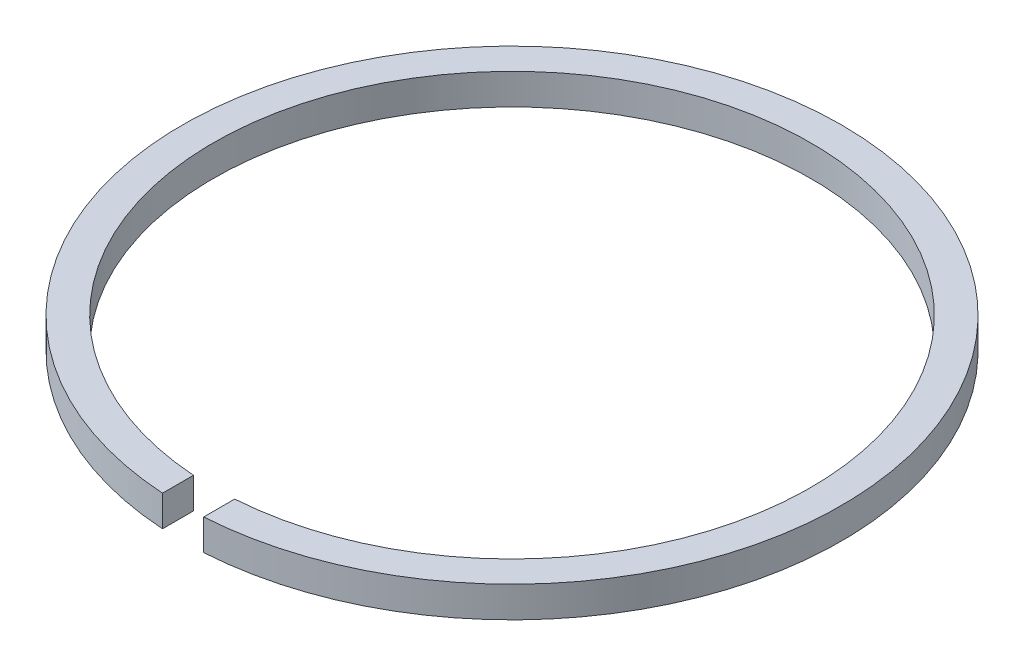
SolidWorks part; units mm, degrees
ref_plane "Front Plane" through (0, 0, 0) normal (0, 0, 1) x (1, 0, 0)
ref_plane "Top Plane" through (0, 0, 0) normal (0, 1, 0) x (1, 0, 0)
ref_plane "Right Plane" through (0, 0, 0) normal (1, 0, 0) x (0, 0, -1)
sketch "Sketch1" plane through (0, 0, 0) normal (0, 1, 0) x (1, 0, 0)
  line L0 (0, 17.4037) -> (0, -20.3096) construction
  line L1 (-1, -14.4655) -> (-1, -15.9687)
  line L2 (1, -14.4655) -> (1, -15.9687)
  arc A0 (1, -15.9687) -> (-1, -15.9687) centre (0, 0) ccw
  arc A1 (1, -14.4655) -> (-1, -14.4655) centre (0, 0) ccw
  dimension "D1" = 32
  dimension "D2" = 29
  dimension "D3" = 1
extrude "Boss-Extrude1" add sketch "Sketch1" along normal mid plane 1.5
